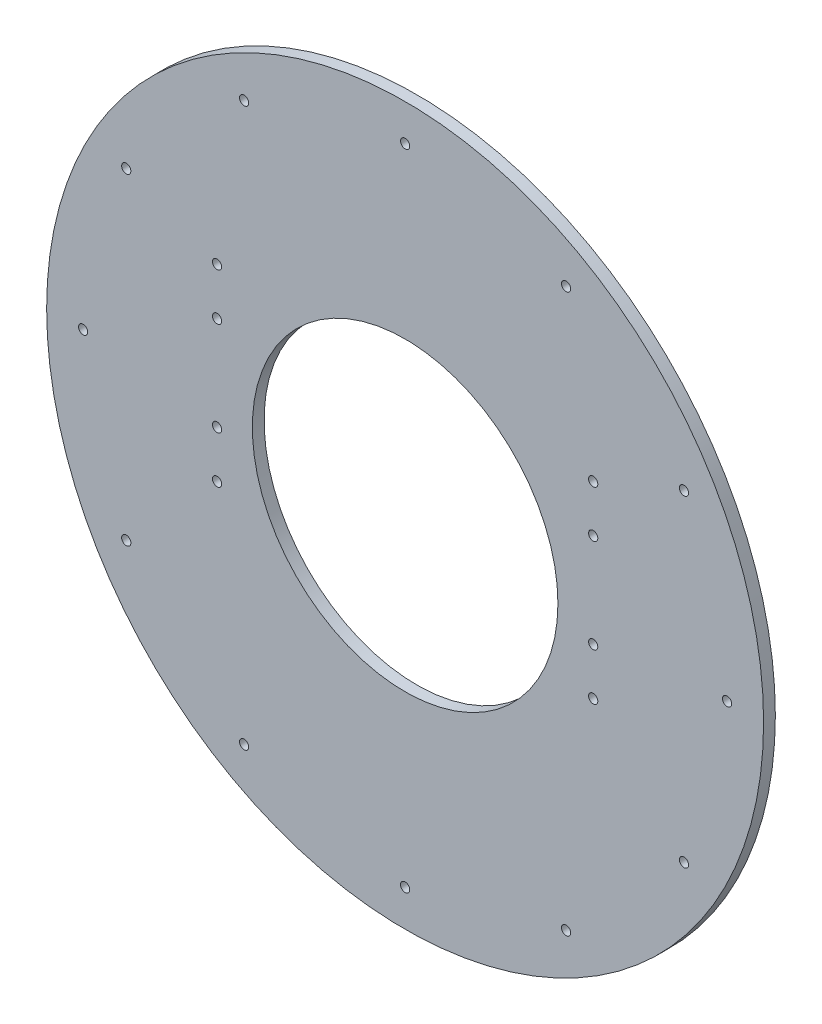
SolidWorks part; units mm, degrees
ref_plane "Front Plane" through (0, 0, 0) normal (1, 0, 0) x (0, 1, 0)
ref_plane "Top Plane" through (0, 0, 0) normal (0, 0, 1) x (0, 1, 0)
ref_plane "Right Plane" through (0, 0, 0) normal (0, 1, 0) x (-1, 0, 0)
sketch "Sketch1" plane through (0, 0, 0) normal (0, 0, 1) x (0, 1, 0)
  circle A0 centre (0, 0) radius 193.675
  circle A1 centre (0, 0) radius 173.9646 construction
  point P4 (-150.6578, 86.9823)
  point P5 (0, 0)
  point P6 (0, 0)
  point P7 (-66.2735, 145.3258)
  point P8 (-86.9823, 150.6578)
  point P9 (0, 173.9646)
  point P10 (86.9823, 150.6578)
  point P11 (150.6578, 86.9823)
  point P12 (173.9646, 0)
  point P13 (150.6578, -86.9823)
  point P14 (86.9823, -150.6578)
  point P15 (0, -173.9646)
  point P16 (-86.9823, -150.6578)
  point P17 (-150.6578, -86.9823)
  point P18 (-173.9646, 0)
  point P19 (0, 0)
  point P20 (0, 0)
  point P21 (0, 0)
  dimension "D1" = 387.35
  dimension "D2" = 347.9292
  dimension "D3" = 12
extrude "Boss-Extrude1" add sketch "Sketch1" along normal blind 6.35
sketch "Sketch2" plane through (0, 0, 6.35) normal (0, 0, 1) x (1, 0, 0)
  point P0 (-150.6578, 86.9823)
  point P2 (-173.9646, 0)
  point P4 (-150.6578, -86.9823)
  point P6 (-86.9823, -150.6578)
  point P8 (0, -173.9646)
  point P10 (86.9823, -150.6578)
  point P12 (150.6578, -86.9823)
  point P14 (173.9646, 0)
  point P16 (150.6578, 86.9823)
  point P18 (86.9823, 150.6578)
  point P20 (0, 173.9646)
  point P22 (-86.9823, 150.6578)
hole_wizard "#9 (0.196) Diameter Hole1" positions "Sketch2" profile "Sketch3" hole size "#9" standard "ANSI Inch" end condition through all
sketch "Sketch3" plane through (-150.6578, 86.9823, 6.35) normal (1, 0, 0) x (0, -1, 0)
  line L0 (0, 0) -> (0, 6.35)
  line L1 (0, 6.35) -> (2.4892, 6.35)
  line L2 (2.4892, 6.35) -> (2.4892, 0)
  line L5 (2.4892, 0) -> (0, 0)
  line L11 (0, -6.35) -> (0, 107.95) construction
  dimension "Thru Hole Dia." = 4.9784
  dimension "Thru Hole Depth" = 6.35
sketch "Sketch5" plane through (0, 0, 6.35) normal (0, 0, 1) x (1, 0, 0)
  line L0 (0, 88.9) -> (0, -88.9) construction
  line L1 (-82.55, -88.9) -> (82.55, -88.9) construction
  line L2 (-82.55, -88.9) -> (-82.55, 88.9) construction
  line L3 (-82.55, 88.9) -> (82.55, 88.9) construction
  line L4 (82.55, -88.9) -> (82.55, 88.9) construction
  line L5 (-82.55, -88.9) -> (82.55, 88.9) construction
  line L6 (-82.55, 88.9) -> (82.55, -88.9) construction
  circle A0 centre (0, 0) radius 82.55
  point P0 (0, 0)
  point P6 (-101.6, -34.925)
  point P7 (-101.6, -9.525)
  point P8 (-101.6, 41.275)
  point P9 (-101.6, 66.675)
  point P18 (101.6, 66.675)
  point P19 (101.6, 41.275)
  point P20 (101.6, -9.525)
  point P21 (101.6, -34.925)
  dimension "D1" = 165.1
  dimension "D2" = 177.8
  dimension "D3" = 19.05
  dimension "D4" = 53.975
  dimension "D5" = 25.4
  dimension "D6" = 25.4
  dimension "D7" = 50.8
extrude "Cut-Extrude1" cut sketch "Sketch5" against normal blind 6.35
sketch "Sketch6" plane through (0, 0, 6.35) normal (0, 0, 1) x (1, 0, 0)
  point P0 (101.6, 66.675)
  point P2 (101.6, 41.275)
  point P4 (101.6, -9.525)
  point P6 (101.6, -34.925)
  point P8 (-101.6, -34.925)
  point P10 (-101.6, -9.525)
  point P12 (-101.6, 41.275)
  point P14 (-101.6, 66.675)
hole_wizard "#9 (0.196) Diameter Hole2" positions "Sketch6" profile "Sketch7" hole size "#9" standard "ANSI Inch" end condition through all
sketch "Sketch7" plane through (101.6, 66.675, 6.35) normal (1, 0, 0) x (0, -1, 0)
  line L0 (0, 0) -> (0, 6.35)
  line L1 (0, 6.35) -> (2.4892, 6.35)
  line L2 (2.4892, 6.35) -> (2.4892, 0)
  line L5 (2.4892, 0) -> (0, 0)
  line L11 (0, -6.35) -> (0, 107.95) construction
  dimension "Thru Hole Dia." = 4.9784
  dimension "Thru Hole Depth" = 6.35
